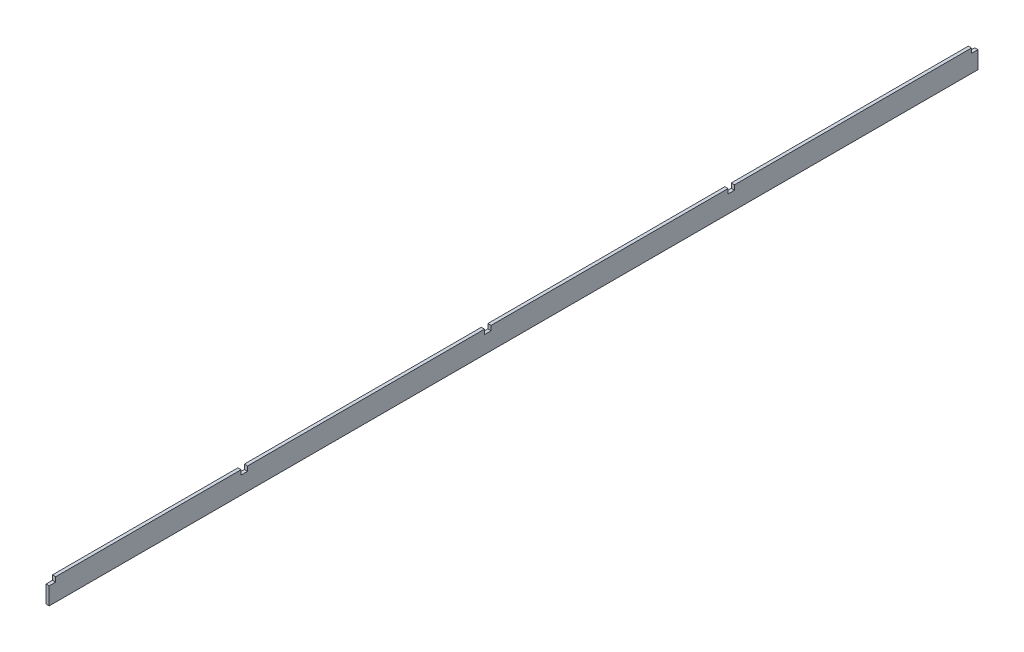
SolidWorks part; units mm, degrees
material "Balsa"
ref_plane "Front Plane" through (0, 0, 0) normal (0, 0, 1) x (1, 0, 0)
ref_plane "Top Plane" through (0, 0, 0) normal (0, 1, 0) x (1, 0, 0)
ref_plane "Right Plane" through (0, 0, 0) normal (1, 0, 0) x (0, 0, -1)
sketch "Sketch2" plane through (336.1904, 0, 0) normal (1, 0, 0) x (0, 0, -1)
  line L0 (0, 145.8414) -> (3.175, 145.8414) construction
  line L1 (0, 145.8414) -> (3.175, 145.8414)
  line L2 (-334.1687, 145.8414) -> (-330.9938, 145.8414) construction
  line L3 (-239.7125, 145.8414) -> (-236.5375, 145.8414) construction
  line L4 (123.0312, 145.8414) -> (119.8563, 145.8414)
  line L5 (119.8563, 145.8414) -> (119.8562, 137.2839)
  line L6 (119.8562, 137.2839) -> (123.0312, 137.2839)
  line L7 (123.0312, 137.2839) -> (123.0312, 145.8414)
  line L8 (123.0312, 145.8414) -> (119.8563, 145.8414)
  line L10 (119.8562, 137.2839) -> (123.0312, 137.2839)
  line L11 (123.0312, 137.2839) -> (123.0312, 145.8414)
  line L12 (-119.8563, 145.8414) -> (-116.6813, 145.8414) construction
  line L13 (-334.1687, 145.8414) -> (-330.9938, 145.8414)
  line L14 (-239.7125, 145.8414) -> (-236.5375, 145.8414)
  line L15 (-119.8563, 145.8414) -> (-116.6813, 145.8414)
  line L16 (-334.1687, 137.2839) -> (-334.1687, 145.8414) construction
  line L17 (-334.1687, 137.2839) -> (-334.1687, 145.8414)
  line L18 (-330.9938, 137.2839) -> (-334.1687, 137.2839) construction
  line L19 (-330.9938, 137.2839) -> (-334.1687, 137.2839)
  line L20 (-330.9938, 137.2839) -> (119.8562, 137.2839)
  line L21 (119.8563, 145.8414) -> (119.8563, 148.1342)
  line L22 (119.8563, 148.1342) -> (3.175, 148.1342)
  line L23 (-330.9938, 148.1342) -> (-330.9938, 145.8414)
  line L24 (-236.5375, 145.8414) -> (-236.5375, 148.1342)
  line L25 (-239.7125, 145.8414) -> (-239.7125, 148.1342)
  line L26 (-116.6813, 145.8414) -> (-116.6813, 148.1342)
  line L27 (-119.8563, 145.8414) -> (-119.8563, 148.1342)
  line L28 (3.175, 145.8414) -> (3.175, 148.1342)
  line L29 (0, 145.8414) -> (0, 148.1342)
  line L30 (0, 148.1342) -> (-116.6813, 148.1342)
  line L31 (-119.8563, 148.1342) -> (-236.5375, 148.1342)
  line L32 (-239.7125, 148.1342) -> (-330.9938, 148.1342)
  dimension "D1" = 0
extrude "Boss-Extrude1" add sketch "Sketch2" along normal up to surface (1.5875 mm away)
